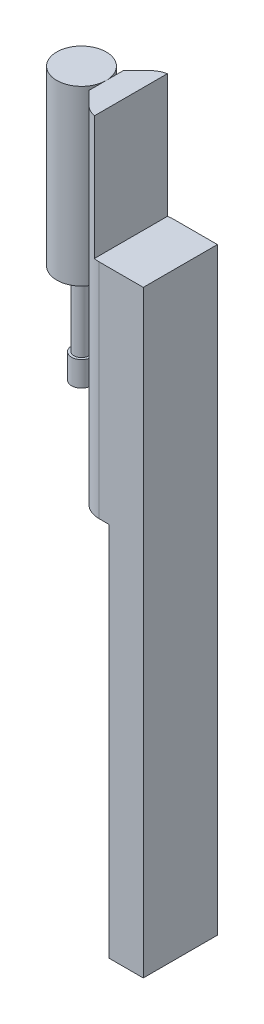
SolidWorks part; units mm, degrees
ref_plane "Front Plane" through (0, 0, 0) normal (0, 0, 1) x (1, 0, 0)
ref_plane "Top Plane" through (0, 0, 0) normal (0, 1, 0) x (1, 0, 0)
ref_plane "Right Plane" through (0, 0, 0) normal (1, 0, 0) x (0, 0, -1)
sketch "Sketch1" plane through (0, 0, 0) normal (0, 1, 0) x (1, 0, 0)
  line L1 (0, 0) -> (30, 0)
  line L2 (0, 0) -> (0, 30)
  line L3 (0, 30) -> (30, 30)
  line L4 (30, 0) -> (30, 30)
  dimension "D1" = 30
  dimension "D2" = 30
extrude "Boss-Extrude1" add sketch "Sketch1" along normal blind 90
sketch "Sketch2" plane through (0, 0, 0) normal (1, 0, 0) x (0, 0, -1)
  line L1 (0, 90) -> (30, 90)
  line L2 (0, 90) -> (0, 140)
  line L3 (0, 140) -> (30, 140)
  line L4 (30, 90) -> (30, 140)
  dimension "D1" = 50
extrude "Boss-Extrude2" add sketch "Sketch2" along normal blind 10
sketch "Sketch3" plane through (0, 140, 0) normal (0, 1, 0) x (1, 0, 0)
  line L0 (0, 15) -> (-10, 15)
  line L1 (0, 30) -> (0, 0) construction
  circle A0 centre (-10, 15) radius 10
  dimension "D1" = 10
extrude "Boss-Extrude3" add sketch "Sketch3" against normal blind 70 separate body
sketch "Sketch4" plane through (0, 70, 0) normal (0, -1, 0) x (1, 0, 0)
  circle A0 centre (-10, -15) radius 3
  dimension "D1" = 6
extrude "Boss-Extrude4" add sketch "Sketch4" along normal blind 30
sketch "Sketch5" plane through (0, 40, 0) normal (0, -1, 0) x (1, 0, 0)
  circle A0 centre (-10, -15) radius 4
  dimension "D1" = 8
extrude "Boss-Extrude5" add sketch "Sketch5" along normal blind 10
chamfer "Chamfer1" distance 8 angle 45 2 edges at (0, 70, -30) (0, 70, 0)
fillet "Fillet1" radius 10 2 edges at (8, 70, -30) (8, 70, 0)
sketch "Sketch6" plane through (0, 0, 0) normal (0, -1, 0) x (1, 0, 0)
  line L0 (30, -30) -> (12.1421, -30) construction
  line L1 (30, 0) -> (16.1901, 0)
  line L2 (30, 0) -> (30, -30)
  line L3 (30, -30) -> (16.1901, -30)
  line L4 (16.1901, 0) -> (16.1901, -30)
extrude "Boss-Extrude6" add sketch "Sketch6" along normal blind 152
